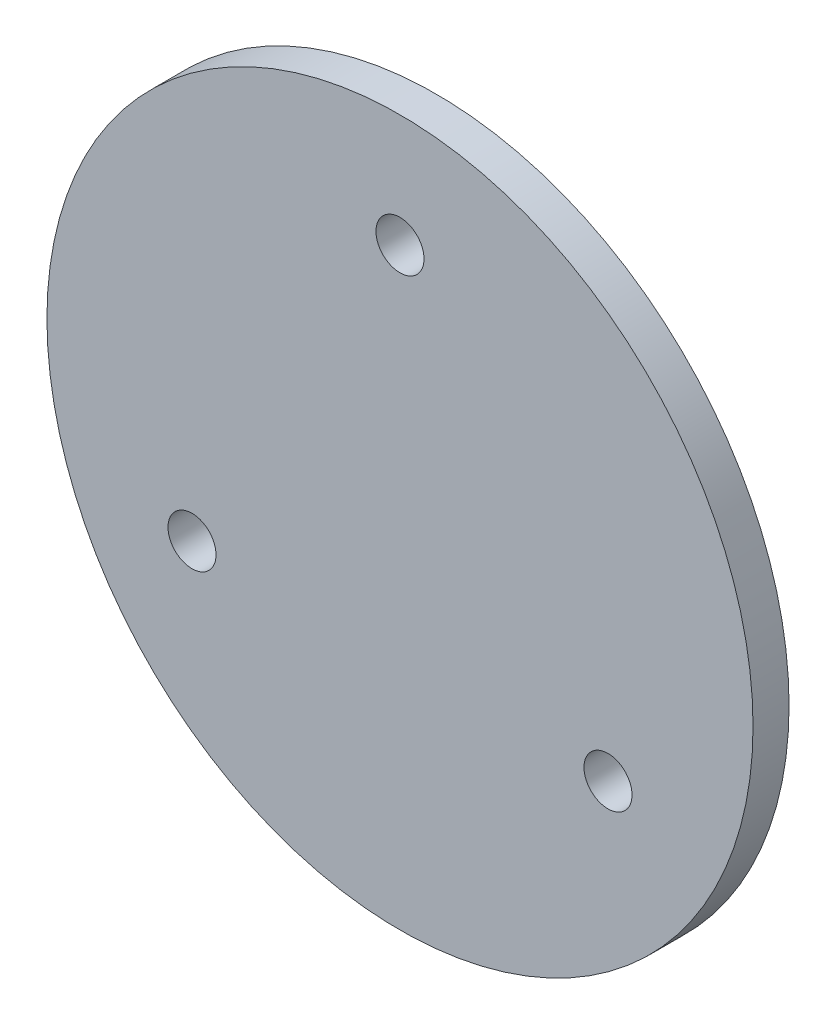
SolidWorks part; units mm, degrees
ref_plane "Front Plane" through (0, 0, 0) normal (0, 0, 1) x (1, 0, 0)
ref_plane "Top Plane" through (0, 0, 0) normal (0, 1, 0) x (1, 0, 0)
ref_plane "Right Plane" through (0, 0, 0) normal (1, 0, 0) x (0, 0, -1)
sketch "Sketch1" plane through (0, 0, 0) normal (0, 0, 1) x (1, 0, 0)
  line L1 (-11.5, 11) -> (11.5, 11)
  line L2 (-11.5, 11) -> (-11.5, -11)
  line L3 (-11.5, -11) -> (11.5, -11)
  line L4 (11.5, 11) -> (11.5, -11)
  line L5 (-11.5, 11) -> (11.5, -11) construction
  line L6 (-11.5, -11) -> (11.5, 11) construction
  point P0 (0, 0)
  dimension "D1" = 22
  dimension "D2" = 23
extrude "Boss-Extrude1" add sketch "Sketch1" along normal blind 5
sketch "Sketch3" plane through (0, 0, 5) normal (0, 0, 1) x (1, 0, 0)
  circle A0 centre (0, 0) radius 29.4
  dimension "D1" = 58.8
extrude "Boss-Extrude2" add sketch "Sketch3" along normal blind 3
sketch "Sketch4" plane through (0, 0, 8) normal (0, 0, 1) x (1, 0, 0)
  line L0 (0, -4.4) -> (0, 4.4) construction
  circle A0 centre (0, 20) radius 2
  circle A1 centre (17.3205, -10) radius 2
  circle A2 centre (-17.3205, -10) radius 2
  point P12 (0, 0)
  dimension "D1" = 4
  dimension "D2" = 20
  dimension "D3" = 3
extrude "Cut-Extrude1" cut sketch "Sketch4" against normal blind 3
